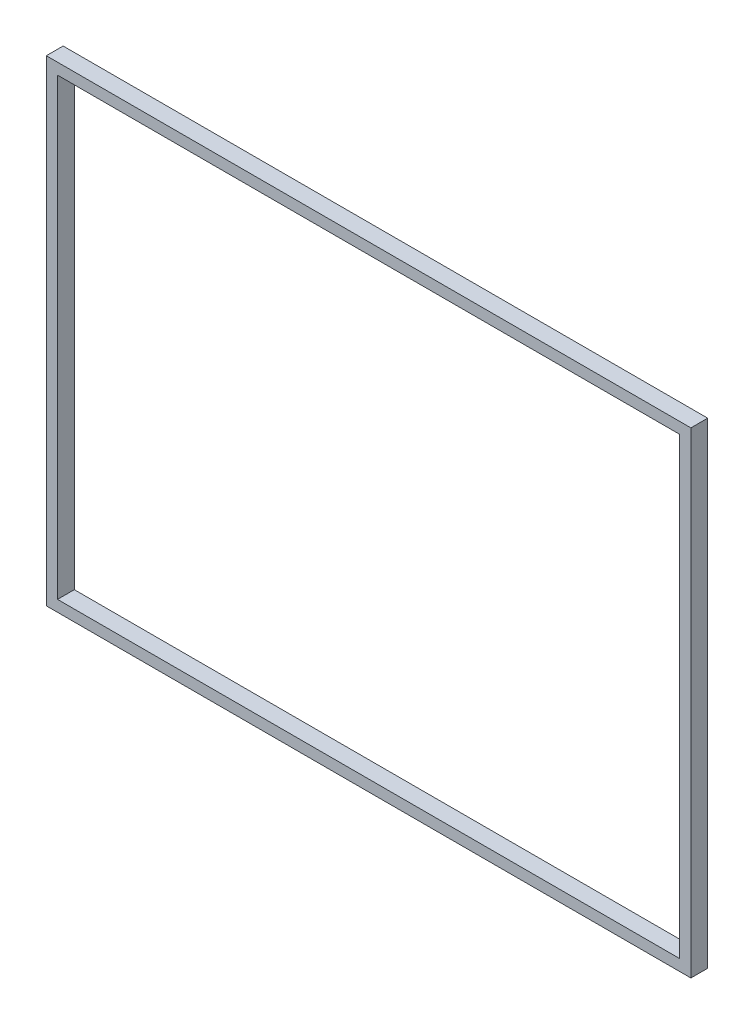
SolidWorks part; units mm, degrees
material "Liga 1060"
ref_plane "Plano frontal" through (0, 0, 0) normal (0, 0, 1) x (1, 0, 0)
ref_plane "Plano superior" through (0, 0, 0) normal (0, 1, 0) x (1, 0, 0)
ref_plane "Plano direito" through (0, 0, 0) normal (1, 0, 0) x (0, 0, -1)
sketch "Esboço1" plane through (0, 0, 0) normal (0, 0, 1) x (1, 0, 0)
  line L1 (-78.5209, 35.7825) -> (36.4791, 35.7825)
  line L2 (-78.5209, 35.7825) -> (-78.5209, -49.2175)
  line L3 (-78.5209, -49.2175) -> (36.4791, -49.2175)
  line L4 (36.4791, 35.7825) -> (36.4791, -49.2175)
  line L5 (-76.5209, 33.7825) -> (34.4791, 33.7825)
  line L6 (-76.5209, 33.7825) -> (-76.5209, -47.2175)
  line L7 (-76.5209, -47.2175) -> (34.4791, -47.2175)
  line L8 (34.4791, 33.7825) -> (34.4791, -47.2175)
  dimension "D1" = 115
  dimension "D2" = 85
  dimension "D3" = 81
  dimension "D4" = 111
  dimension "D5" = 2
  dimension "D6" = 2
extrude "Ressalto-extrusão1" add sketch "Esboço1" along normal blind 3
sketch "Esboço2" plane through (0, 0, 3) normal (0, 0, 1) x (1, 0, 0)
  line L1 (-76.5209, 33.7825) -> (34.4791, 33.7825)
  line L2 (-76.5209, 33.7825) -> (-76.5209, -47.2175)
  line L3 (-76.5209, -47.2175) -> (34.4791, -47.2175)
  line L4 (34.4791, 33.7825) -> (34.4791, -47.2175)
